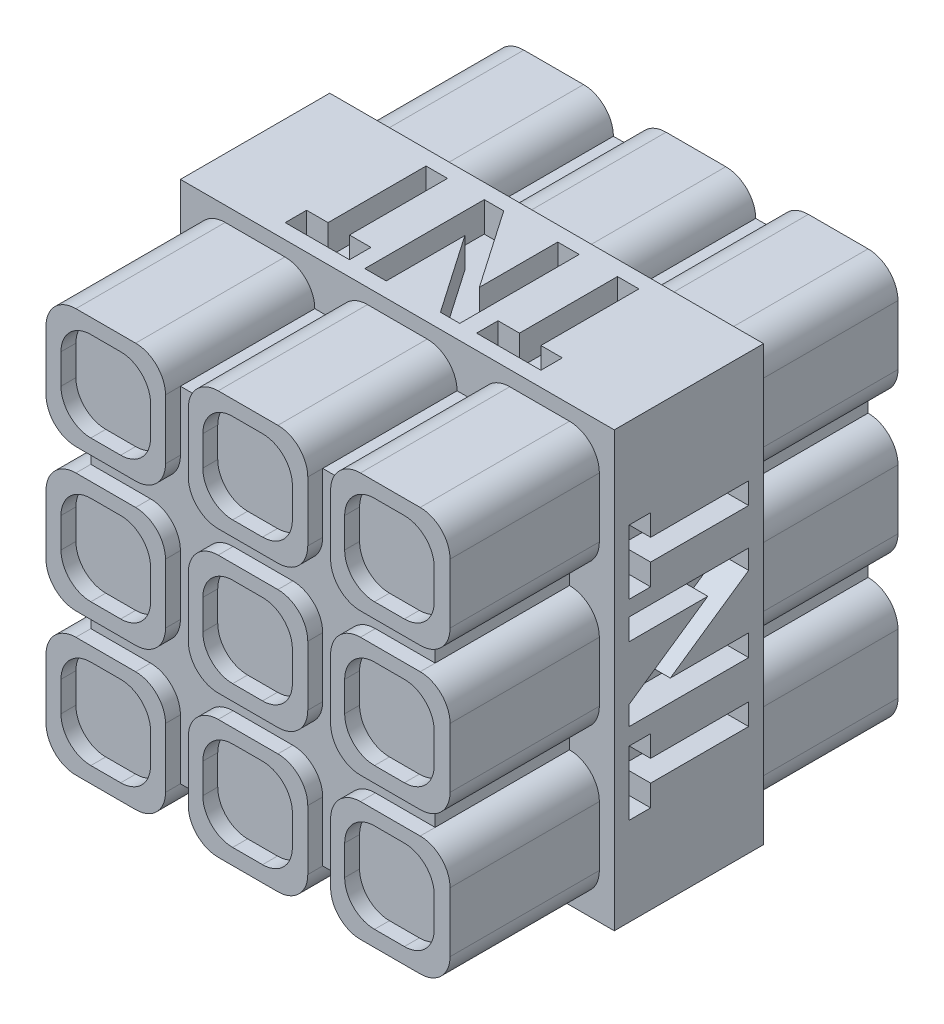
SolidWorks part; units mm, degrees
ref_plane "Front Plane" through (0, 0, 0) normal (0, 0, 1) x (1, 0, 0)
ref_plane "Top Plane" through (0, 0, 0) normal (0, 1, 0) x (1, 0, 0)
ref_plane "Right Plane" through (0, 0, 0) normal (1, 0, 0) x (0, 0, -1)
sketch "Sketch1" plane through (0, 0, 0) normal (0, 0, 1) x (1, 0, 0)
  line L2 (0, -2) -> (0, -6)
  line L3 (2, -8) -> (6, -8)
  line L6 (11.5294, -8) -> (15.5294, -8)
  line L10 (21.0588, -8) -> (25.0588, -8)
  line L11 (27.0588, -2) -> (27.0588, -6)
  line L19 (27.0588, 7.5294) -> (27.0588, 3.5294)
  line L20 (11.5294, 19.0588) -> (15.5294, 19.0588)
  line L24 (21.0588, 19.0588) -> (25.0588, 19.0588)
  line L27 (27.0588, 17.0588) -> (27.0588, 13.0588)
  line L29 (0, 7.5294) -> (0, 3.5294)
  line L32 (2, 19.0588) -> (6, 19.0588)
  line L33 (0, 17.0588) -> (0, 13.0588)
  line L36 (17.5294, 17.0588) -> (19.0588, 17.0588)
  line L37 (8, 17.0588) -> (9.5294, 17.0588)
  line L38 (2, 11.0588) -> (2, 9.5294)
  line L39 (8, -6) -> (9.5294, -6)
  line L40 (25.0588, 11.0588) -> (25.0588, 9.5294)
  line L41 (2, 11.0588) -> (6, 11.0588) [skipped]
  line L43 (2, 1.5294) -> (6, 1.5294) [skipped]
  line L44 (9.5294, -2) -> (9.5294, -6) [skipped]
  line L45 (19.0588, -2) -> (19.0588, -6) [skipped]
  line L46 (21.0588, 1.5294) -> (25.0588, 1.5294) [skipped]
  line L47 (11.5294, 1.5294) -> (15.5294, 1.5294) [skipped]
  line L48 (9.5294, 7.5294) -> (9.5294, 3.5294) [skipped]
  line L49 (11.5294, 11.0588) -> (15.5294, 11.0588) [skipped]
  line L50 (9.5294, 17.0588) -> (9.5294, 13.0588) [skipped]
  line L51 (19.0588, 7.5294) -> (19.0588, 3.5294) [skipped]
  line L52 (19.0588, 17.0588) -> (19.0588, 13.0588) [skipped]
  line L53 (21.0588, 11.0588) -> (25.0588, 11.0588) [skipped]
  line L54 (25.0588, 1.5294) -> (25.0588, 0)
  line L55 (2, 1.5294) -> (2, 0)
  line L56 (17.5294, -6) -> (19.0588, -6)
  arc A0 (0, -6) -> (2, -8) centre (2, -6) ccw
  arc A1 (6, -8) -> (8, -6) centre (6, -6) ccw
  arc A3 (2, 0) -> (0, -2) centre (2, -2) ccw
  arc A4 (9.5294, -6) -> (11.5294, -8) centre (11.5294, -6) ccw
  arc A5 (15.5294, -8) -> (17.5294, -6) centre (15.5294, -6) ccw
  arc A8 (19.0588, -6) -> (21.0588, -8) centre (21.0588, -6) ccw
  arc A9 (25.0588, -8) -> (27.0588, -6) centre (25.0588, -6) ccw
  arc A10 (25.0588, 0) -> (27.0588, -2) centre (25.0588, -2) cw
  arc A17 (25.0588, 1.5294) -> (27.0588, 3.5294) centre (25.0588, 3.5294) ccw
  arc A18 (25.0588, 9.5294) -> (27.0588, 7.5294) centre (25.0588, 7.5294) cw
  arc A22 (15.5294, 19.0588) -> (17.5294, 17.0588) centre (15.5294, 17.0588) cw
  arc A23 (11.5294, 19.0588) -> (9.5294, 17.0588) centre (11.5294, 17.0588) ccw
  arc A25 (25.0588, 11.0588) -> (27.0588, 13.0588) centre (25.0588, 13.0588) ccw
  arc A26 (25.0588, 19.0588) -> (27.0588, 17.0588) centre (25.0588, 17.0588) cw
  arc A27 (21.0588, 19.0588) -> (19.0588, 17.0588) centre (21.0588, 17.0588) ccw
  arc A28 (0, 3.5294) -> (2, 1.5294) centre (2, 3.5294) ccw
  arc A31 (2, 9.5294) -> (0, 7.5294) centre (2, 7.5294) ccw
  arc A32 (0, 13.0588) -> (2, 11.0588) centre (2, 13.0588) ccw
  arc A34 (6, 19.0588) -> (8, 17.0588) centre (6, 17.0588) cw
  arc A35 (2, 19.0588) -> (0, 17.0588) centre (2, 17.0588) ccw
  arc A36 (21.0588, 0) -> (19.0588, -2) centre (21.0588, -2) ccw [skipped]
  arc A38 (11.5294, 0) -> (9.5294, -2) centre (11.5294, -2) ccw [skipped]
  arc A39 (6, 1.5294) -> (8, 3.5294) centre (6, 3.5294) ccw [skipped]
  arc A40 (9.5294, 3.5294) -> (11.5294, 1.5294) centre (11.5294, 3.5294) ccw [skipped]
  arc A41 (15.5294, 1.5294) -> (17.5294, 3.5294) centre (15.5294, 3.5294) ccw [skipped]
  arc A42 (19.0588, 3.5294) -> (21.0588, 1.5294) centre (21.0588, 3.5294) ccw [skipped]
  arc A43 (11.5294, 9.5294) -> (9.5294, 7.5294) centre (11.5294, 7.5294) ccw [skipped]
  arc A44 (6, 11.0588) -> (8, 13.0588) centre (6, 13.0588) ccw [skipped]
  arc A45 (9.5294, 13.0588) -> (11.5294, 11.0588) centre (11.5294, 13.0588) ccw [skipped]
  arc A46 (21.0588, 9.5294) -> (19.0588, 7.5294) centre (21.0588, 7.5294) ccw [skipped]
  arc A47 (19.0588, 13.0588) -> (21.0588, 11.0588) centre (21.0588, 13.0588) ccw [skipped]
  arc A48 (15.5294, 11.0588) -> (17.5294, 13.0588) centre (15.5294, 13.0588) ccw [skipped]
  point P11 (8, 0)
  point P14 (0, 0)
  dimension "D2" = 2
  dimension "D1" = 8
  dimension "D3" = 3
  dimension "D4" = 3
extrude "Boss-Extrude1" add sketch "Sketch1" along normal blind 30
ref_plane "Plane1" through (0, 0, 10) normal (0, 0, 1) x (1, 0, 0)
sketch "Sketch2" plane through (0, 0, 10) normal (0, 0, 1) x (1, 0, 0)
  line L1 (-1, 20.0588) -> (28.0588, 20.0588)
  line L2 (-1, 20.0588) -> (-1, -9)
  line L3 (-1, -9) -> (28.0588, -9)
  line L4 (28.0588, 20.0588) -> (28.0588, -9)
  line L6 (15.5294, 19.0588) -> (11.5294, 19.0588) construction
  line L7 (0, 7.5294) -> (0, 3.5294) construction
  line L8 (27.0588, 3.5294) -> (27.0588, 7.5294) construction
  line L9 (11.5294, -8) -> (15.5294, -8) construction
  point P4 (27.6711, -8.3691)
  point P5 (-0.6173, 19.6369)
  point P6 (24.1369, 19.0588)
  point P9 (27.0588, 19.0588)
  point P10 (0, 19.0588)
  point P11 (0, -8)
  point P12 (0, 0)
  point P13 (0, -8)
  dimension "D1" = 1
  dimension "D2" = 1
  dimension "D3" = 1
  dimension "D4" = 1
extrude "Boss-Extrude2" add sketch "Sketch2" along normal blind 10
sketch "Sketch3" plane through (-1, 0, 0) normal (-1, 0, 0) x (0, 0, 1)
  line L0 (11, 20.0588) -> (11, -9) construction
  line L1 (20, 20.0588) -> (10, 20.0588) construction
  line L2 (20, -9) -> (10, -9) construction
  line L3 (10, -15.9824) -> (10, 15.9824) construction
  text T0 "TNT" font "Century Gothic" height 8
  point P3 (11.2636, 12.4782)
  point P4 (11.3547, 20.0588)
  point P7 (11.3547, -9)
  dimension "D1" = 1
extrude "Cut-Extrude1" cut sketch "Sketch3" against normal blind 2
pattern_circular "CirPattern1" count 4 over 360 about axis through (13.5294, 5.5294, 0) along (0, 0, 1) of "Cut-Extrude1"
sketch "Sketch5" plane through (0, 0, 30) normal (0, 0, 1) x (1, 0, 0)
  line L0 (6, 19.0588) -> (2, 19.0588) construction
  line L1 (3, 18.0588) -> (5, 18.0588)
  line L2 (1, 16.0588) -> (1, 14.0588)
  line L3 (3, 12.0588) -> (5, 12.0588)
  line L4 (7, 16.0588) -> (7, 14.0588)
  line L5 (0, 17.0588) -> (0, 13.0588) construction
  line L6 (12.5, 18.0588) -> (14.5, 18.0588)
  line L7 (10.5, 16.0588) -> (10.5, 14.0588)
  line L8 (12.5, 12.0588) -> (14.5, 12.0588)
  line L9 (16.5, 16.0588) -> (16.5, 14.0588)
  line L10 (22, 18.0588) -> (24, 18.0588)
  line L11 (20, 16.0588) -> (20, 14.0588)
  line L12 (22, 12.0588) -> (24, 12.0588)
  line L13 (26, 16.0588) -> (26, 14.0588)
  line L14 (12.5, 8.5588) -> (14.5, 8.5588)
  line L15 (10.5, 6.5588) -> (10.5, 4.5588)
  line L16 (12.5, 2.5588) -> (14.5, 2.5588)
  line L17 (16.5, 6.5588) -> (16.5, 4.5588)
  line L18 (22, 8.5588) -> (24, 8.5588)
  line L19 (20, 6.5588) -> (20, 4.5588)
  line L20 (22, 2.5588) -> (24, 2.5588)
  line L21 (26, 6.5588) -> (26, 4.5588)
  line L22 (12.5, -0.9412) -> (14.5, -0.9412)
  line L23 (10.5, -2.9412) -> (10.5, -4.9412)
  line L24 (12.5, -6.9412) -> (14.5, -6.9412)
  line L25 (16.5, -2.9412) -> (16.5, -4.9412)
  line L26 (22, -0.9412) -> (24, -0.9412)
  line L27 (20, -2.9412) -> (20, -4.9412)
  line L28 (22, -6.9412) -> (24, -6.9412)
  line L29 (26, -2.9412) -> (26, -4.9412)
  line L30 (3, 8.5588) -> (5, 8.5588)
  line L31 (1, 6.5588) -> (1, 4.5588)
  line L32 (3, 2.5588) -> (5, 2.5588)
  line L33 (7, 6.5588) -> (7, 4.5588)
  line L34 (3, -0.9412) -> (5, -0.9412)
  line L35 (1, -2.9412) -> (1, -4.9412)
  line L36 (3, -6.9412) -> (5, -6.9412)
  line L37 (7, -2.9412) -> (7, -4.9412)
  arc A0 (1, 14.0588) -> (3, 12.0588) centre (3, 14.0588) ccw
  arc A1 (5, 12.0588) -> (7, 14.0588) centre (5, 14.0588) ccw
  arc A2 (5, 18.0588) -> (7, 16.0588) centre (5, 16.0588) cw
  arc A3 (3, 18.0588) -> (1, 16.0588) centre (3, 16.0588) ccw
  arc A4 (10.5, 14.0588) -> (12.5, 12.0588) centre (12.5, 14.0588) ccw
  arc A5 (14.5, 12.0588) -> (16.5, 14.0588) centre (14.5, 14.0588) ccw
  arc A6 (14.5, 18.0588) -> (16.5, 16.0588) centre (14.5, 16.0588) cw
  arc A7 (12.5, 18.0588) -> (10.5, 16.0588) centre (12.5, 16.0588) ccw
  arc A8 (20, 14.0588) -> (22, 12.0588) centre (22, 14.0588) ccw
  arc A9 (24, 12.0588) -> (26, 14.0588) centre (24, 14.0588) ccw
  arc A10 (24, 18.0588) -> (26, 16.0588) centre (24, 16.0588) cw
  arc A11 (22, 18.0588) -> (20, 16.0588) centre (22, 16.0588) ccw
  arc A12 (10.5, 4.5588) -> (12.5, 2.5588) centre (12.5, 4.5588) ccw
  arc A13 (14.5, 2.5588) -> (16.5, 4.5588) centre (14.5, 4.5588) ccw
  arc A14 (14.5, 8.5588) -> (16.5, 6.5588) centre (14.5, 6.5588) cw
  arc A15 (12.5, 8.5588) -> (10.5, 6.5588) centre (12.5, 6.5588) ccw
  arc A16 (20, 4.5588) -> (22, 2.5588) centre (22, 4.5588) ccw
  arc A17 (24, 2.5588) -> (26, 4.5588) centre (24, 4.5588) ccw
  arc A18 (24, 8.5588) -> (26, 6.5588) centre (24, 6.5588) cw
  arc A19 (22, 8.5588) -> (20, 6.5588) centre (22, 6.5588) ccw
  arc A20 (10.5, -4.9412) -> (12.5, -6.9412) centre (12.5, -4.9412) ccw
  arc A21 (14.5, -6.9412) -> (16.5, -4.9412) centre (14.5, -4.9412) ccw
  arc A22 (14.5, -0.9412) -> (16.5, -2.9412) centre (14.5, -2.9412) cw
  arc A23 (12.5, -0.9412) -> (10.5, -2.9412) centre (12.5, -2.9412) ccw
  arc A24 (20, -4.9412) -> (22, -6.9412) centre (22, -4.9412) ccw
  arc A25 (24, -6.9412) -> (26, -4.9412) centre (24, -4.9412) ccw
  arc A26 (24, -0.9412) -> (26, -2.9412) centre (24, -2.9412) cw
  arc A27 (22, -0.9412) -> (20, -2.9412) centre (22, -2.9412) ccw
  arc A28 (1, 4.5588) -> (3, 2.5588) centre (3, 4.5588) ccw
  arc A29 (5, 2.5588) -> (7, 4.5588) centre (5, 4.5588) ccw
  arc A30 (5, 8.5588) -> (7, 6.5588) centre (5, 6.5588) cw
  arc A31 (3, 8.5588) -> (1, 6.5588) centre (3, 6.5588) ccw
  arc A32 (1, -4.9412) -> (3, -6.9412) centre (3, -4.9412) ccw
  arc A33 (5, -6.9412) -> (7, -4.9412) centre (5, -4.9412) ccw
  arc A34 (5, -0.9412) -> (7, -2.9412) centre (5, -2.9412) cw
  arc A35 (3, -0.9412) -> (1, -2.9412) centre (3, -2.9412) ccw
  point P10 (1, 12.0588)
  point P17 (1, 18.0588)
  dimension "D4" = 2
  dimension "D1" = 1
  dimension "D2" = 6
  dimension "D3" = 1
  dimension "D5" = 3
  dimension "D6" = 3
extrude "Cut-Extrude2" cut sketch "Sketch5" against normal blind 1
sketch "Sketch6" plane through (0, 0, 30) normal (0, 0, 1) x (1, 0, 0)
  line L0 (2, 11.0588) -> (25.0588, 11.0588)
  line L1 (25.0588, 11.0588) -> (25.0588, 9.5294)
  line L2 (25.0588, 9.5294) -> (2, 9.5294)
  line L3 (2, 9.5294) -> (2, 11.0588)
  line L4 (2, 1.5294) -> (25.0588, 1.5294)
  line L5 (25.0588, 1.5294) -> (25.0588, 0)
  line L6 (25.0588, 0) -> (2, 0)
  line L7 (2, 1.5294) -> (2, 0) construction
  line L8 (2, 1.5294) -> (2, 0) construction
  line L9 (2, 0) -> (2, 1.5294)
extrude "Cut-Extrude3" cut sketch "Sketch6" against normal blind 1
sketch "Sketch7" plane through (0, 0, 30) normal (0, 0, 1) x (1, 0, 0)
  line L0 (8, 17.0588) -> (8, -6)
  line L1 (8, -6) -> (9.5294, -6)
  line L2 (9.5294, -6) -> (9.5294, 17.0588)
  line L3 (9.5294, 17.0588) -> (8, 17.0588) construction
  line L4 (9.5294, 17.0588) -> (8, 17.0588)
  line L5 (17.5294, 17.0588) -> (19.0588, 17.0588)
  line L6 (19.0588, 17.0588) -> (19.0588, -6)
  line L7 (19.0588, -6) -> (17.5294, -6)
  line L8 (17.5294, -6) -> (17.5294, 17.0588)
extrude "Cut-Extrude4" cut sketch "Sketch7" against normal blind 1
fillet "Fillet1" radius 2 16 edges at (19.0588, 1.5294, 29.5) (9.5294, 1.5294, 29.5) (8, 1.5294, 29.5) (17.5294, 1.5294, 29.5) (19.0588, 0, 29.5) (17.5294, 0, 29.5) (9.5294, 0, 29.5) (8, 0, 29.5) (9.5294, 9.5294, 29.5) (19.0588, 9.5294, 29.5) (17.5294, 9.5294, 29.5) (19.0588, 11.0588, 29.5) (17.5294, 11.0588, 29.5) (9.5294, 11.0588, 29.5) (8, 9.5294, 29.5) (8, 11.0588, 29.5)
